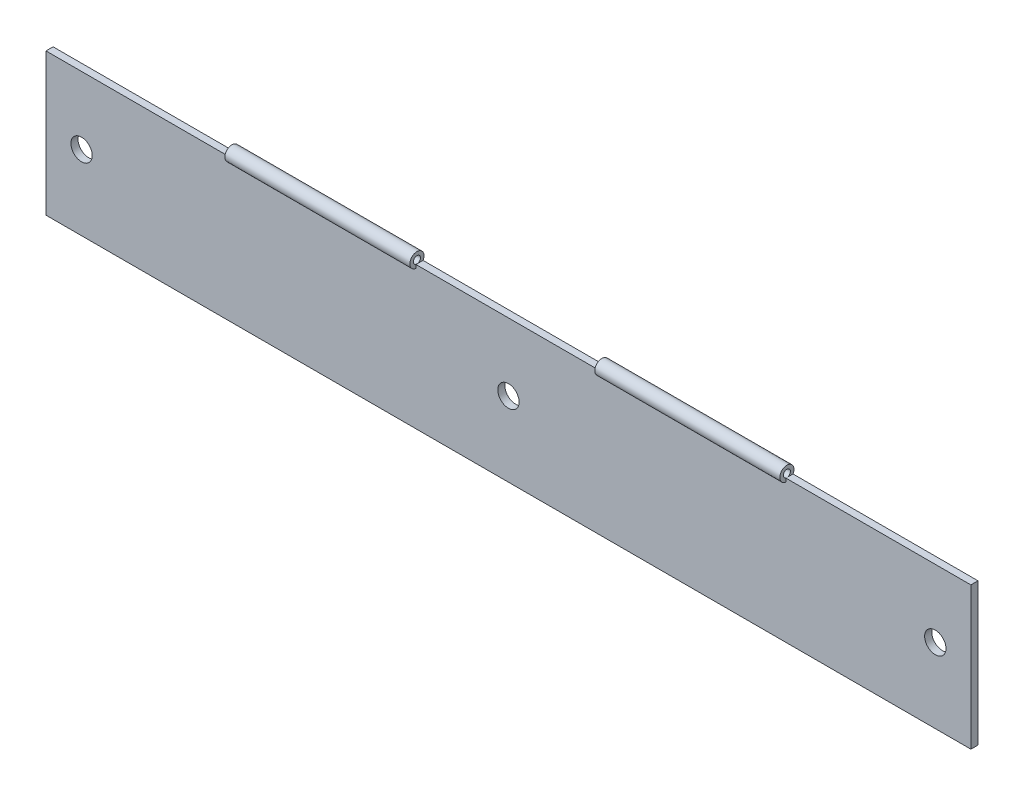
SolidWorks part; units mm, degrees
ref_plane "Front Plane" through (0, 0, 0) normal (0, 0, 1) x (1, 0, 0)
ref_plane "Top Plane" through (0, 0, 0) normal (0, 1, 0) x (1, 0, 0)
ref_plane "Right Plane" through (0, 0, 0) normal (1, 0, 0) x (0, 0, -1)
sketch "Sketch1" plane through (0, 0, 0) normal (0, 0, 1) x (1, 0, 0)
  line L1 (0, 0) -> (130, 0)
  line L2 (0, 0) -> (0, 20)
  line L3 (0, 20) -> (130, 20)
  line L4 (130, 0) -> (130, 20)
  circle A0 centre (65, 10.5) radius 1.5
  circle A1 centre (5, 10.5) radius 1.5
  circle A2 centre (125, 10.5) radius 1.5
  dimension "D3" = 3
  dimension "D4" = 3
  dimension "D5" = 3
  dimension "D1" = 130
  dimension "D2" = 20
  dimension "D6" = 60
  dimension "D7" = 60
  dimension "D8" = 65
  dimension "D9" = 9.5
extrude "Boss-Extrude1" add sketch "Sketch1" along normal blind 1
sketch "Sketch3" plane through (0, 0, 0) normal (1, 0, 0) x (0, 0, -1)
  circle A0 centre (-0.8635, 20.5043) radius 1
  circle A1 centre (-0.8635, 20.5043) radius 0.5
  dimension "D1" = 2
  dimension "D2" = 1
extrude "Boss-Extrude2" add sketch "Sketch3" along normal blind 26 from offset 26
sketch "Sketch4" plane through (0, 0, 0) normal (0, 0, 1) x (1, 0, 0)
  line L0 (-7.6845, 20.652) -> (134.5741, 20.652) construction
pattern_linear "LPattern1" count 2 spacing 52 along (1, 0, 0) of "Boss-Extrude2"
